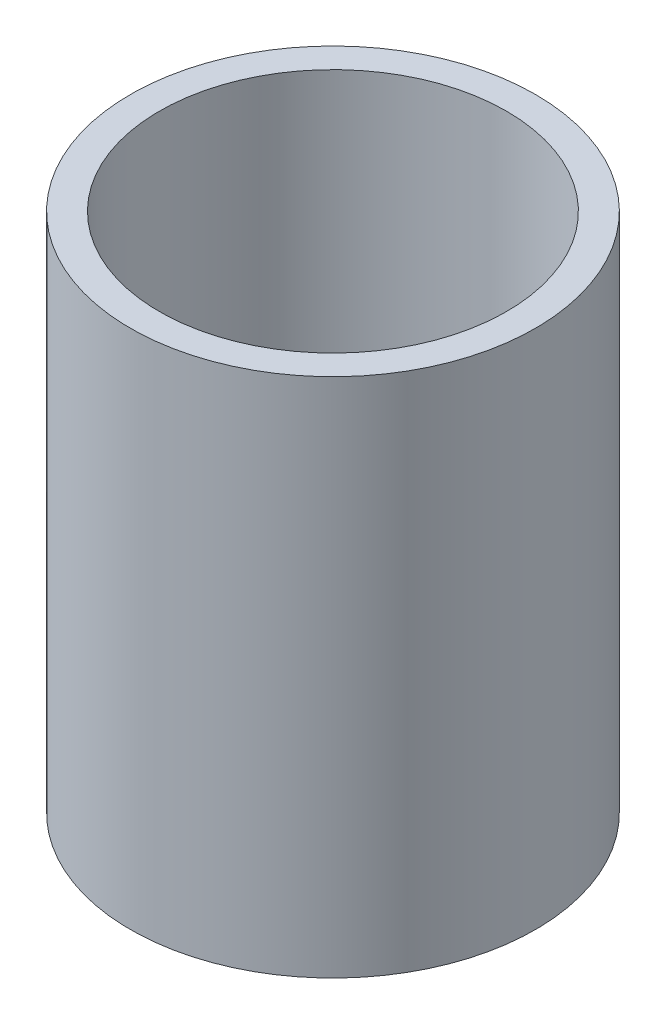
SolidWorks part; units mm, degrees
ref_plane "前视基准面" through (0, 0, 0) normal (0, 0, 1) x (1, 0, 0)
ref_plane "上视基准面" through (0, 0, 0) normal (0, 1, 0) x (1, 0, 0)
ref_plane "右视基准面" through (0, 0, 0) normal (1, 0, 0) x (0, 0, -1)
other "Configuration Table"
sketch "草图1" plane through (0, 0, 0) normal (0, 1, 0) x (1, 0, 0)
  circle A0 centre (0, 0) radius 70
extrude "凸台-拉伸1" add sketch "草图1" along normal blind 180
sketch "草图2" plane through (0, 0, 0) normal (0, 1, 0) x (1, 0, 0)
  circle A0 centre (0, 0) radius 60
extrude "切除-拉伸1" cut sketch "草图2" along normal blind 360
